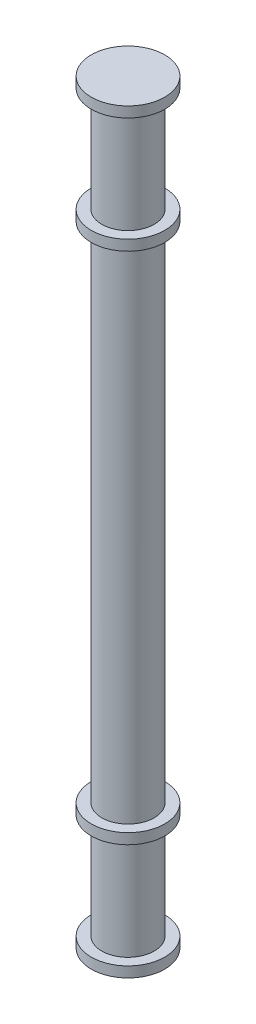
SolidWorks part; units mm, degrees
ref_plane "前视基准面" through (0, 0, 0) normal (0, 0, 1) x (1, 0, 0)
ref_plane "上视基准面" through (0, 0, 0) normal (0, 1, 0) x (1, 0, 0)
ref_plane "右视基准面" through (0, 0, 0) normal (1, 0, 0) x (0, 0, -1)
sketch "草图1" plane through (0, 0, 0) normal (0, 1, 0) x (1, 0, 0)
  circle A0 centre (0, -1.1566) radius 5
extrude "凸台-拉伸1" add sketch "草图1" along normal blind 144
sketch "草图4" plane through (0, 144, 0) normal (0, 1, 0) x (1, 0, 0)
  circle A1 centre (0, -1.1566) radius 5
  circle A3 centre (0, -1.1566) radius 5
  dimension "D1" = 0
extrude "拉伸-薄壁1" add sketch "草图4" against normal blind 2 thin contours A3
sketch "草图5" plane through (0, 0, 0) normal (0, -1, 0) x (1, 0, 0)
  circle A1 centre (0, 1.1566) radius 5
  circle A2 centre (0, 1.1566) radius 5
  dimension "D1" = 0
extrude "拉伸-薄壁2" add sketch "草图5" against normal blind 2 thin
sketch "草图6" plane through (0, 144, 0) normal (0, 1, 0) x (1, 0, 0)
  circle A0 centre (0, -1.1566) radius 5
extrude "拉伸-薄壁3" add sketch "草图6" against normal blind 2 from offset 22 separate body thin offset against normal yes
sketch "草图7" plane through (0, 0, 0) normal (0, -1, 0) x (-1, 0, 0)
  circle A0 centre (0, -1.1566) radius 5
extrude "拉伸-薄壁4" add sketch "草图7" against normal blind 2 from offset 22 thin offset against normal yes
